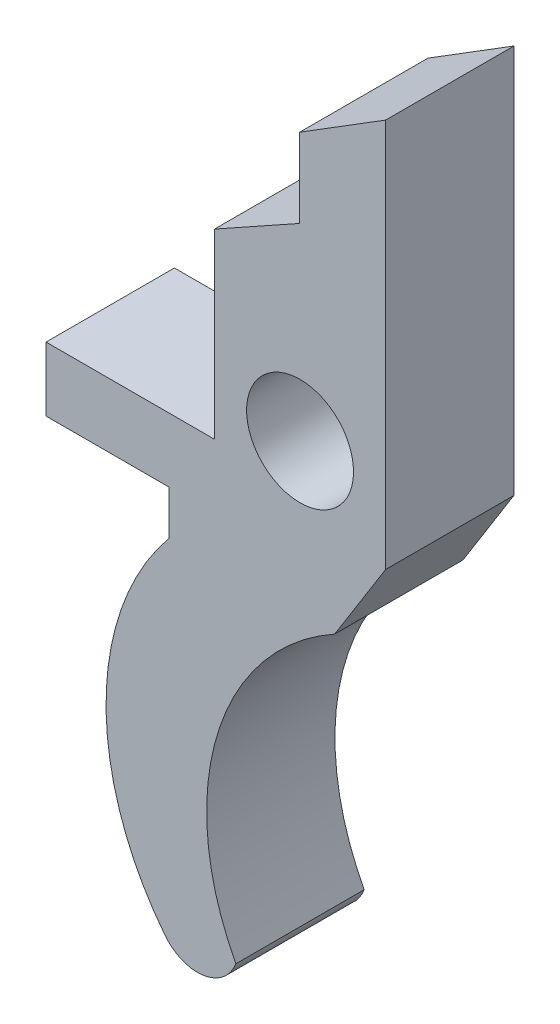
SolidWorks part; units mm, degrees
ref_plane "정면" through (0, 0, 0) normal (0, 0, 1) x (1, 0, 0)
ref_plane "윗면" through (0, 0, 0) normal (0, 1, 0) x (1, 0, 0)
ref_plane "우측면" through (0, 0, 0) normal (1, 0, 0) x (0, 0, -1)
sketch "스케치1" plane through (0, 0, 0) normal (0, 0, 1) x (1, 0, 0)
  line L0 (-0.0187, 12.4999) -> (4, 15)
  line L1 (4, 15) -> (4, -3.2023)
  line L2 (4, -3.2023) -> (1.619, -7.0059)
  line L3 (1.619, -7.0059) -> (-6.1296, -7.0059)
  line L4 (-6.1296, -7.0059) -> (-6.1296, -4.928)
  line L5 (-6.1296, -4.928) -> (-11.8771, -4.928)
  line L6 (-11.8771, -4.928) -> (-11.8771, -1.928)
  line L7 (-11.8771, -1.928) -> (-4, -1.928)
  line L8 (-4, -1.928) -> (-4, 6.5859)
  line L9 (-4, 6.5859) -> (-0.0187, 8.8049)
  line L10 (-0.0187, 8.8049) -> (-0.0187, 12.4999)
  circle A0 centre (0, 0) radius 4
  circle A1 centre (0, 0) radius 2.5
  arc A2 (1.619, -7.0059) -> (-3, -22.6682) centre (7.2836, -17.1887) ccw
  arc A3 (-6.1296, -7.0059) -> (-6.3027, -23.1876) centre (3.8143, -15.2041) ccw
  arc A4 (-6.3027, -23.1876) -> (-3, -22.6682) centre (-4.7973, -21.9997) ccw
  point P8 (-4, 0)
  point P15 (4, 0)
  dimension "D1" = 8
  dimension "D3" = 5
  dimension "D2" = 15
  dimension "D4" = 3
extrude "보스-돌출1" add sketch "스케치1" along normal blind 6 contours A0 L8 L7 L6 L5 L4 L3 L2 L1 | A0 A1 | A0 L1 L0 L10 L9 L8 | A3 A4 A2 L3
